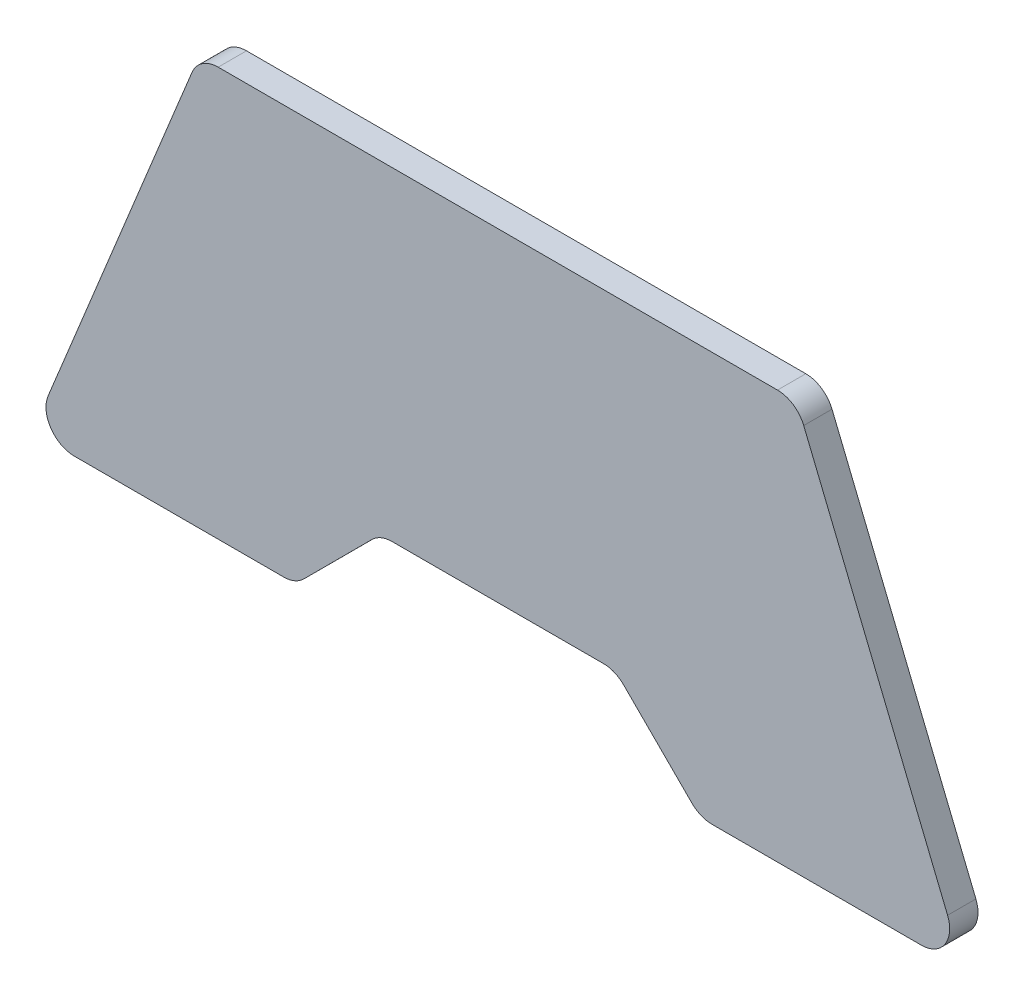
SolidWorks part; units mm, degrees
ref_plane "Plan de face" through (0, 0, 0) normal (0, 0, 1) x (1, 0, 0)
ref_plane "Plan de dessus" through (0, 0, 0) normal (0, 1, 0) x (1, 0, 0)
ref_plane "Plan de droite" through (0, 0, 0) normal (1, 0, 0) x (0, 0, -1)
sketch "Esquisse1" plane through (0, 0, 0) normal (0, 0, 1) x (1, 0, 0)
  line L8 (18.6789, 0) -> (-18.6789, 0)
  line L9 (-22.2167, -1.4667) -> (-34.2683, -13.5333)
  line L10 (-37.806, -15) -> (-74.7892, -15)
  line L11 (22.2123, -1.4623) -> (34.3028, -13.5377)
  line L12 (37.8361, -15) -> (74.8229, -15)
  line L13 (-79.4178, -8.109) -> (-54.0033, 54.0973)
  line L14 (-49.3747, 57.2063) -> (49.4084, 57.2063)
  line L15 (54.037, 54.0973) -> (79.4515, -8.109)
  line L16 (0.0169, 57.2063) -> (0, 0) construction
  arc A0 (-34.2683, -13.5333) -> (-37.806, -15) centre (-37.806, -10) cw
  arc A1 (-18.6789, 0) -> (-22.2167, -1.4667) centre (-18.6789, -5) ccw
  arc A2 (22.2123, -1.4623) -> (18.6789, 0) centre (18.6789, -5) ccw
  arc A3 (37.8361, -15) -> (34.3028, -13.5377) centre (37.8361, -10) cw
  arc A4 (54.037, 54.0973) -> (49.4084, 57.2063) centre (49.4084, 52.2063) ccw
  arc A5 (-49.3747, 57.2063) -> (-54.0033, 54.0973) centre (-49.3747, 52.2063) ccw
  arc A6 (79.4515, -8.109) -> (74.8229, -15) centre (74.8229, -10) cw
  arc A7 (-79.4178, -8.109) -> (-74.7892, -15) centre (-74.7892, -10) ccw
  point P4 (0, 0)
  point P12 (-35.7331, -15)
  point P15 (-20.7518, 0)
  point P18 (20.7482, 0)
  point P21 (35.7669, -15)
  point P24 (52.7669, 57.2063)
  point P27 (-52.7331, 57.2063)
  point P30 (82.2669, -15)
  point P33 (-82.2331, -15)
  dimension "D10" = 5
  dimension "D1" = 46.5
  dimension "D2" = 46.5
  dimension "D3" = 41.5
  dimension "D4" = 15
  dimension "D5" = 15
  dimension "D6" = 21.2
  dimension "D7" = 78
  dimension "D8" = 78
  dimension "D9" = 105.5
extrude "Boss.-Extru.1" add sketch "Esquisse1" along normal blind 5
sketch "Esquisse2" plane through (0, 0, 5) normal (0, 0, 1) x (1, 0, 0)
  line L0 (0.0169, 57.2063) -> (0, 0) construction
  line L1 (49.4084, 57.2063) -> (-49.3747, 57.2063) construction
